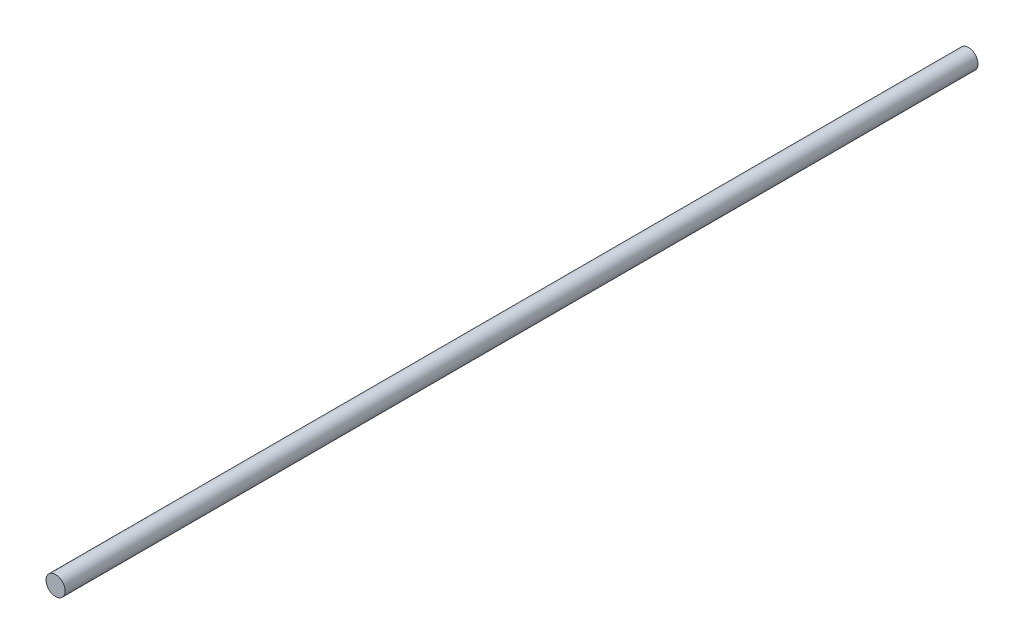
SolidWorks part; units mm, degrees
ref_plane "Front Plane" through (0, 0, 0) normal (0, 0, 1) x (1, 0, 0)
ref_plane "Top Plane" through (0, 0, 0) normal (0, 1, 0) x (1, 0, 0)
ref_plane "Right Plane" through (0, 0, 0) normal (1, 0, 0) x (0, 0, -1)
sketch "Sketch1" plane through (0, 0, 0) normal (0, 0, 1) x (1, 0, 0)
  circle A0 centre (0, 0) radius 0.5
  dimension "D1" = 1
extrude "Boss-Extrude1" add sketch "Sketch1" along normal mid plane 47.752
